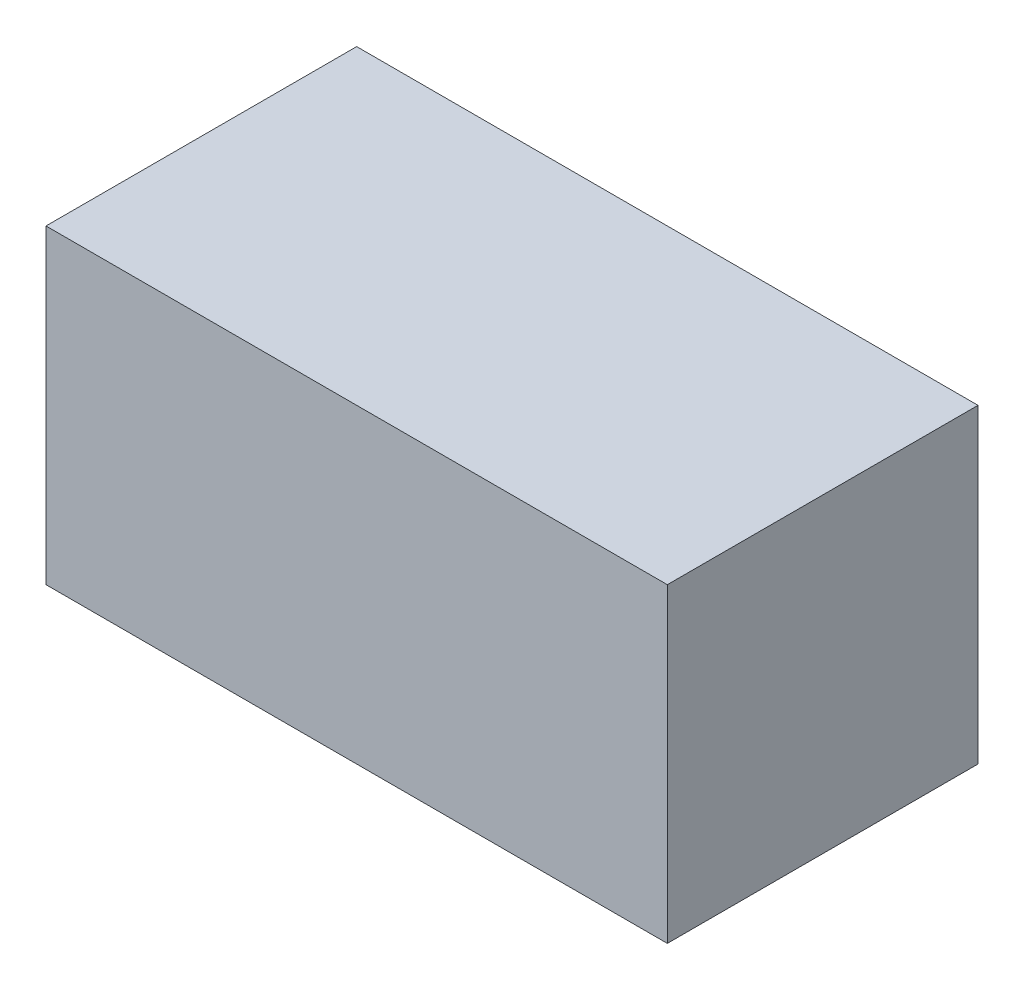
SolidWorks part; units mm, degrees
ref_plane "Front Plane" through (0, 0, 0) normal (0, 0, 1) x (1, 0, 0)
ref_plane "Top Plane" through (0, 0, 0) normal (0, 1, 0) x (1, 0, 0)
ref_plane "Right Plane" through (0, 0, 0) normal (1, 0, 0) x (0, 0, -1)
sketch "Sketch1" plane through (0, 0, 0) normal (0, 1, 0) x (1, 0, 0)
  line L1 (0, 0) -> (0.4, 0)
  line L2 (0, 0) -> (0, 0.2)
  line L3 (0, 0.2) -> (0.4, 0.2)
  line L4 (0.4, 0) -> (0.4, 0.2)
  dimension "D1" = 0.4
  dimension "D2" = 0.2
extrude "Boss-Extrude1" add sketch "Sketch1" along normal blind 0.2
